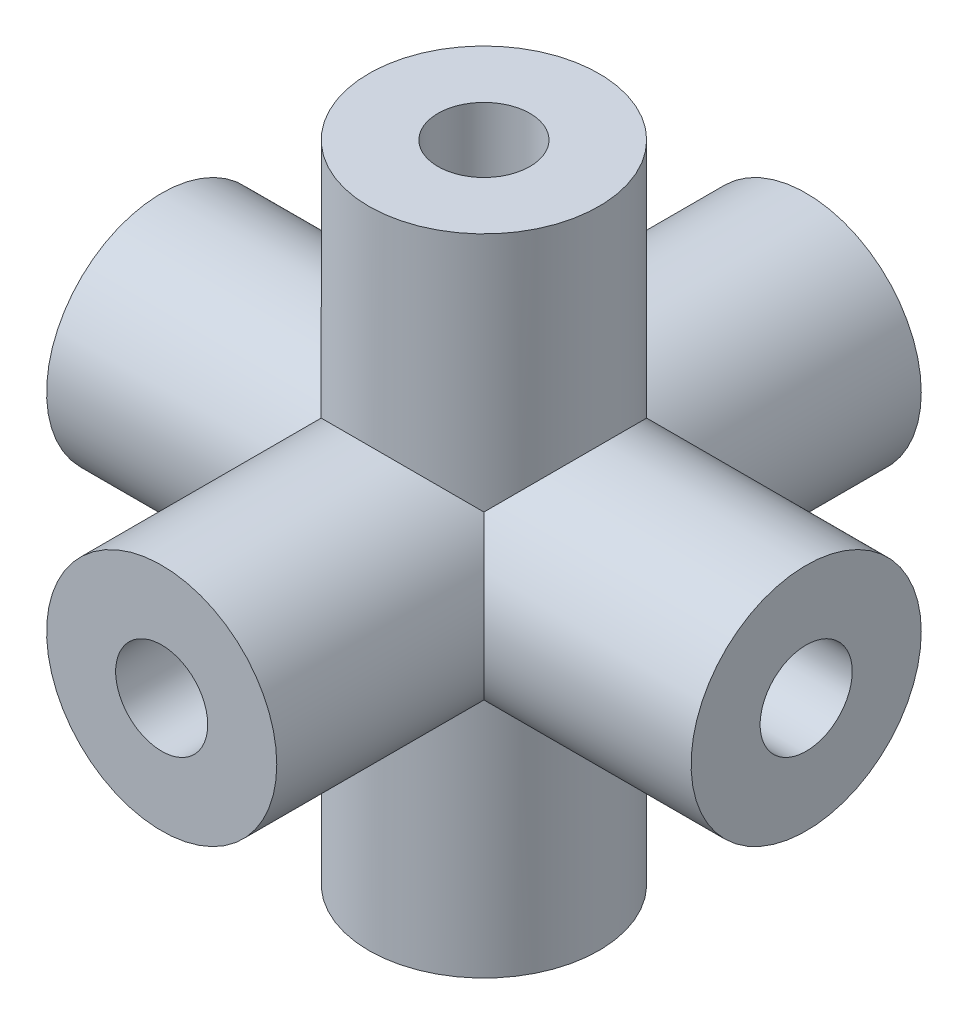
SolidWorks part; units mm, degrees
material "PW100:Mi:0:299:Ar:0:-1:C1:1:2:3:Re:19:"
ref_plane "Front" through (0, 0, 0) normal (0, 0, 1) x (1, 0, 0)
ref_plane "Top" through (0, 0, 0) normal (0, 1, 0) x (1, 0, 0)
ref_plane "Right" through (0, 0, 0) normal (1, 0, 0) x (0, 0, -1)
sketch "Sketch1" plane through (0, 0, 0) normal (0, 0, 1) x (1, 0, 0)
  circle A0 centre (0, 0) radius 2.5
extrude "Base-Extrude" add sketch "Sketch1" along normal mid plane 14
sketch "Sketch2" plane through (0, 0, 0) normal (0, 1, 0) x (1, 0, 0)
  circle A0 centre (0, 0) radius 2.5
sketch "Sketch3" plane through (0, 0, 0) normal (1, 0, 0) x (0, 0, -1)
  circle A0 centre (0, 0) radius 2.5
extrude "Boss-Extrude3" add sketch "Sketch2" along normal mid plane 14
extrude "Boss-Extrude4" add sketch "Sketch3" along normal mid plane 14
sketch "Sketch8" plane through (7, 0, 0) normal (1, 0, 0) x (0, 0, -1)
  circle A0 centre (0, 0) radius 1
extrude "Cut-Extrude2" cut sketch "Sketch8" against normal blind 3
pattern_circular "CirPattern4" count 4 over 360
pattern_circular "CirPattern5" count 4 over 360
sketch "Sketch12" plane through (0, 0, 4) normal (0, 0, 1) x (1, 0, 0)
  point P0 (0, 0)
sketch "Sketch13" plane through (4, 0, 0) normal (1, 0, 0) x (0, 0, -1)
  point P0 (0, 0)
sketch "Sketch14" plane through (0, 0, -4) normal (0, 0, -1) x (-1, 0, 0)
  point P0 (0, 0)
sketch "Sketch15" plane through (0, 4, 0) normal (0, 1, 0) x (-1, 0, 0)
  point P0 (0, 0)
sketch "Sketch16" plane through (-4, 0, 0) normal (-1, 0, 0) x (0, 0, 1)
  point P0 (0, 0)
sketch "Sketch17" plane through (0, -4, 0) normal (0, -1, 0) x (1, 0, 0)
  point P0 (0, 0)
